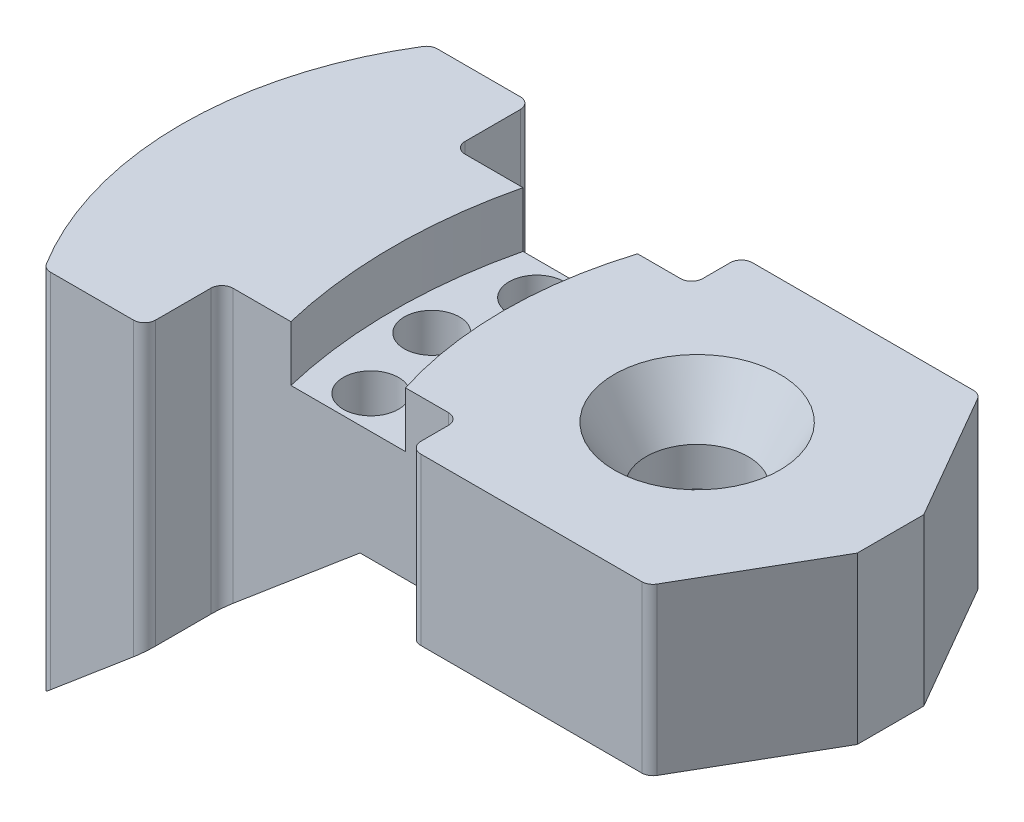
SolidWorks part; units mm, degrees
material "AISI 1020"
ref_plane "Front Plane" through (0, 0, 0) normal (0, 0, 1) x (1, 0, 0)
ref_plane "Top Plane" through (0, 0, 0) normal (0, 1, 0) x (1, 0, 0)
ref_plane "Right Plane" through (0, 0, 0) normal (1, 0, 0) x (0, 0, -1)
sketch "Sketch3" plane through (0, 0, 0) normal (0, 1, 0) x (1, 0, 0)
  line L0 (0, -6.0192) -> (0, 6.0192)
  line L1 (0, 6.0192) -> (-13.2679, 29)
  line L2 (-15, 30) -> (-55, 30)
  line L3 (-57, 28) -> (-57, 23)
  line L4 (-59, 21) -> (-98, 21)
  line L5 (-100, 23) -> (-100, 33)
  line L6 (-102, 35) -> (-117, 35)
  line L7 (-70.5839, 0) -> (70.5839, 0) construction
  line L8 (-102, -35) -> (-117, -35)
  line L9 (-100, -23) -> (-100, -33)
  line L10 (-59, -21) -> (-98, -21)
  line L11 (-57, -28) -> (-57, -23)
  line L12 (-15, -30) -> (-55, -30)
  line L13 (0, -6.0192) -> (-13.2679, -29)
  arc A0 (-118.7037, 34.0476) -> (-118.7037, -34.0476) centre (-63.3344, 0) ccw
  arc A1 (-117, 35) -> (-118.7037, 34.0476) centre (-117, 33) ccw
  arc A2 (-100, 33) -> (-102, 35) centre (-102, 33) ccw
  arc A3 (-98, 21) -> (-100, 23) centre (-98, 23) cw
  arc A4 (-55, 30) -> (-57, 28) centre (-55, 28) ccw
  arc A5 (-13.2679, 29) -> (-15, 30) centre (-15, 28) ccw
  arc A6 (-57, 23) -> (-59, 21) centre (-59, 23) cw
  arc A7 (-57, -23) -> (-59, -21) centre (-59, -23) ccw
  arc A8 (-13.2679, -29) -> (-15, -30) centre (-15, -28) cw
  arc A9 (-55, -30) -> (-57, -28) centre (-55, -28) cw
  arc A10 (-98, -21) -> (-100, -23) centre (-98, -23) ccw
  arc A11 (-100, -33) -> (-102, -35) centre (-102, -33) cw
  arc A12 (-117, -35) -> (-118.7037, -34.0476) centre (-117, -33) cw
  point P43 (0, 0)
  dimension "D1" = 65
  dimension "D2" = 2
  dimension "D3" = 2
  dimension "D4" = 100
  dimension "D5" = 15
  dimension "D6" = 43
  dimension "D7" = 15
  dimension "D8" = 30
  dimension "D9" = 60
  dimension "D10" = 70
  dimension "D11" = 10
extrude "Boss-Extrude2" add sketch "Sketch3" along normal blind 75
sketch "Sketch4" plane through (0, 0, 0) normal (0, 0, 1) x (1, 0, 0)
  line L0 (0, 45) -> (-75, 45)
  line L1 (0, 75) -> (0, 0) construction
  line L2 (-75, 45) -> (-128.3344, 0)
  line L3 (-128.3344, 0) -> (0, 0)
  line L4 (0, 0) -> (0, 45)
  dimension "D1" = 45
  dimension "D2" = 75
extrude "Cut-Extrude1" cut sketch "Sketch4" against normal mid plane 100
sketch "Sketch5" plane through (0, 0, 0) normal (0, 0, 1) x (1, 0, 0)
  line L0 (-35, 75) -> (-50, 75)
  line L1 (-55, 75) -> (-15, 75) construction
  line L2 (-50, 75) -> (-44.2265, 65)
  line L3 (-44.2265, 65) -> (-44.2265, 57.9904)
  line L4 (-44.2265, 57.9904) -> (-42.5, 55)
  line L5 (-42.5, 55) -> (-42.5, 45)
  line L6 (-55, 45) -> (-15, 45) construction
  line L7 (-35, 75) -> (-35, 45)
  line L8 (-35, 45) -> (-42.5, 45)
  line L9 (0, 75) -> (0, 45) construction
  dimension "D1" = 35
  dimension "D2" = 15
  dimension "D3" = 30
  dimension "D4" = 10
  dimension "D5" = 10
  dimension "D6" = 7.5
revolve "Cut-Revolve1" cut sketch "Sketch5" angle 360 about L7
sketch "Sketch6" plane through (0, 75, 0) normal (0, 1, 0) x (1, 0, 0)
  line L0 (-55.9086, 42.1216) -> (-57.7895, 68.9954)
  line L1 (-58.5391, -38.382) -> (-76.1349, -47.9946)
  arc A0 (-55.9086, 42.1216) -> (-58.5391, -38.382) centre (0, 0) ccw
  arc A1 (-57.7895, 68.9954) -> (-76.1349, -47.9946) centre (0, 0) ccw
  dimension "D1" = 70
  dimension "D2" = 90
extrude "Cut-Extrude2" cut sketch "Sketch6" against normal blind 10
sketch "Sketch7" plane through (0, 65, 0) normal (0, 1, 0) x (1, 0, 0)
  line L0 (0, 0) -> (-128.3344, 0) construction
  circle A0 centre (-79.0331, 15) radius 5
  circle A1 centre (-83, 0) radius 5
  circle A2 centre (-79.0331, -15) radius 5
  arc A3 (-118.7037, 34.0476) -> (-118.7037, -34.0476) centre (-63.3344, 0) ccw construction
  arc A4 (-66.7757, 21) -> (-66.7757, -21) centre (0, 0) ccw construction
  point P12 (0, 0)
  dimension "D1" = 10
  dimension "D2" = 10
  dimension "D3" = 10
  dimension "D4" = 15
  dimension "D5" = 15
  dimension "D6" = 13
extrude "Cut-Extrude3" cut sketch "Sketch7" against normal blind 10
sketch "Sketch8" plane through (0, 0, 0) normal (1, 0, 0) x (0, 0, -1)
  line L0 (6.0192, 45) -> (-6.0192, 45) construction
  circle A0 centre (0, 25) radius 7.5
  dimension "D1" = 15
  dimension "D2" = 20
extrude "Cut-Extrude4" cut sketch "Sketch8" against normal through all
